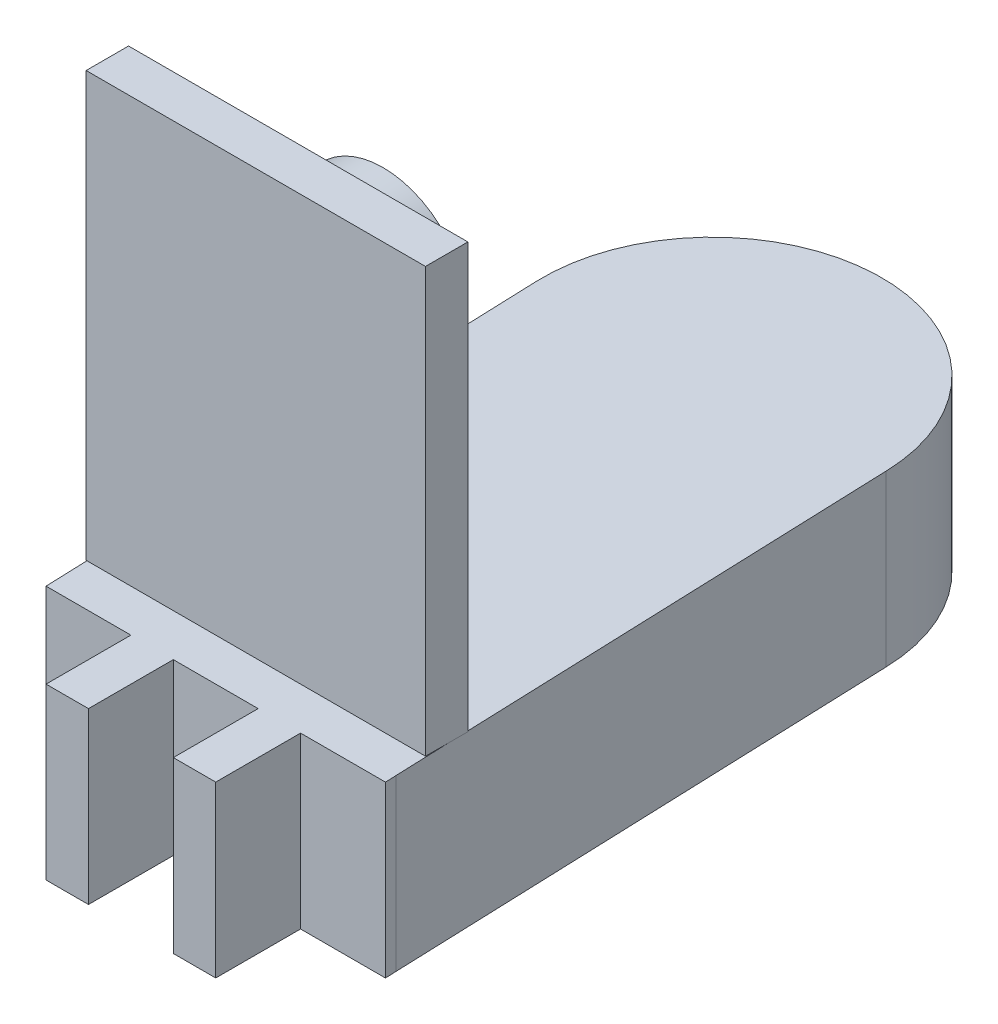
SolidWorks part; units mm, degrees
ref_plane "Front Plane" through (0, 0, 0) normal (0, 0, 1) x (1, 0, 0)
ref_plane "Top Plane" through (0, 0, 0) normal (0, 1, 0) x (1, 0, 0)
ref_plane "Right Plane" through (0, 0, 0) normal (1, 0, 0) x (0, 0, -1)
sketch "Sketch1" plane through (0, 0, 0) normal (0, 1, 0) x (1, 0, 0)
  line L0 (0, 0) -> (3.7583, -60.739) construction
  line L1 (19.9932, 0.5221) -> (22.1863, -59.4378)
  line L2 (-19.9863, -0.739) -> (-17.7679, -60.739)
  line L3 (-17.7679, -60.739) -> (22.2321, -60.739)
  line L6 (-7.7679, -70.739) -> (-7.7679, -60.739)
  line L7 (-7.7679, -60.739) -> (1.12, -60.739)
  line L10 (12.2321, -70.739) -> (12.2321, -60.3413)
  line L11 (-6.0563, -70.739) -> (-2.7679, -70.739)
  line L12 (-2.7679, -60.739) -> (7.2321, -60.739)
  line L13 (-2.7679, -60.739) -> (-2.7679, -70.739)
  line L15 (7.2321, -60.739) -> (7.2321, -70.739)
  line L16 (-2.7679, -60.739) -> (2.2321, -65.739) construction
  line L17 (-2.7679, -70.739) -> (7.2321, -60.739) construction
  line L18 (-7.7679, -70.739) -> (-2.7679, -70.739)
  line L19 (7.2321, -70.739) -> (12.2321, -70.739)
  arc A0 (19.9932, 0.5221) -> (-19.9863, -0.739) centre (0, 0) ccw
  arc A1 (22.2321, -60.739) -> (22.1863, -59.4378) centre (3.7583, -60.739) ccw
  point P3 (1.1092, -30)
  point P8 (2.2321, -65.739)
extrude "Boss-Extrude1" add sketch "Sketch1" along normal blind 20
sketch "Sketch2" plane through (0, 20, 0) normal (0, 1, 0) x (1, 0, 0)
  line L4 (-18.0452, -55.7387) -> (21.9548, -55.7387)
  line L5 (-18.0452, -55.7387) -> (-18.0452, -50.7387)
  line L6 (-18.0452, -50.7387) -> (21.9548, -50.7387)
  line L7 (21.9548, -55.7387) -> (21.9548, -50.7387)
  line L8 (-18.0452, -55.7387) -> (21.9548, -50.7387) construction
  line L9 (-18.0452, -50.7387) -> (21.9548, -55.7387) construction
  point P6 (1.9548, -53.2387)
extrude "Boss-Extrude2" add sketch "Sketch2" along normal blind 50
sketch "Sketch3" plane through (0, -50, 50.7387) normal (0, 0, -1) x (-1, 0, 0)
  circle A0 centre (-1.9548, 102.5961) radius 10
extrude "Boss-Extrude3" add sketch "Sketch3" along normal blind 10
sketch "Sketch4" plane through (0, 70, 0) normal (0, 1, 0) x (1, 0, 0)
